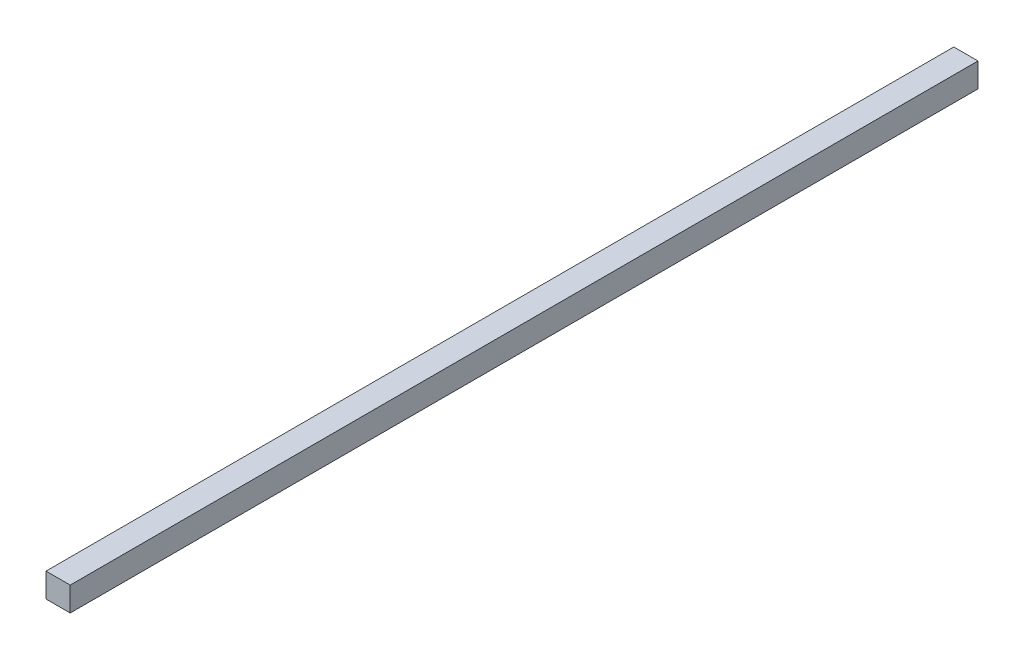
SolidWorks part; units mm, degrees
ref_plane "前视基准面" through (0, 0, 0) normal (0, 0, 1) x (1, 0, 0)
ref_plane "上视基准面" through (0, 0, 0) normal (0, 1, 0) x (1, 0, 0)
ref_plane "右视基准面" through (0, 0, 0) normal (1, 0, 0) x (0, 0, -1)
sketch "草图1" plane through (0, 0, 0) normal (0, 0, 1) x (1, 0, 0)
  line L1 (-10, -10) -> (10, -10)
  line L2 (-10, -10) -> (-10, 10)
  line L3 (-10, 10) -> (10, 10)
  line L4 (10, -10) -> (10, 10)
  line L5 (-10, -10) -> (10, 10) construction
  line L6 (-10, 10) -> (10, -10) construction
  point P0 (0, 0)
  dimension "D1" = 20
  dimension "D2" = 20
extrude "凸台-拉伸1" add sketch "草图1" along normal blind 750
